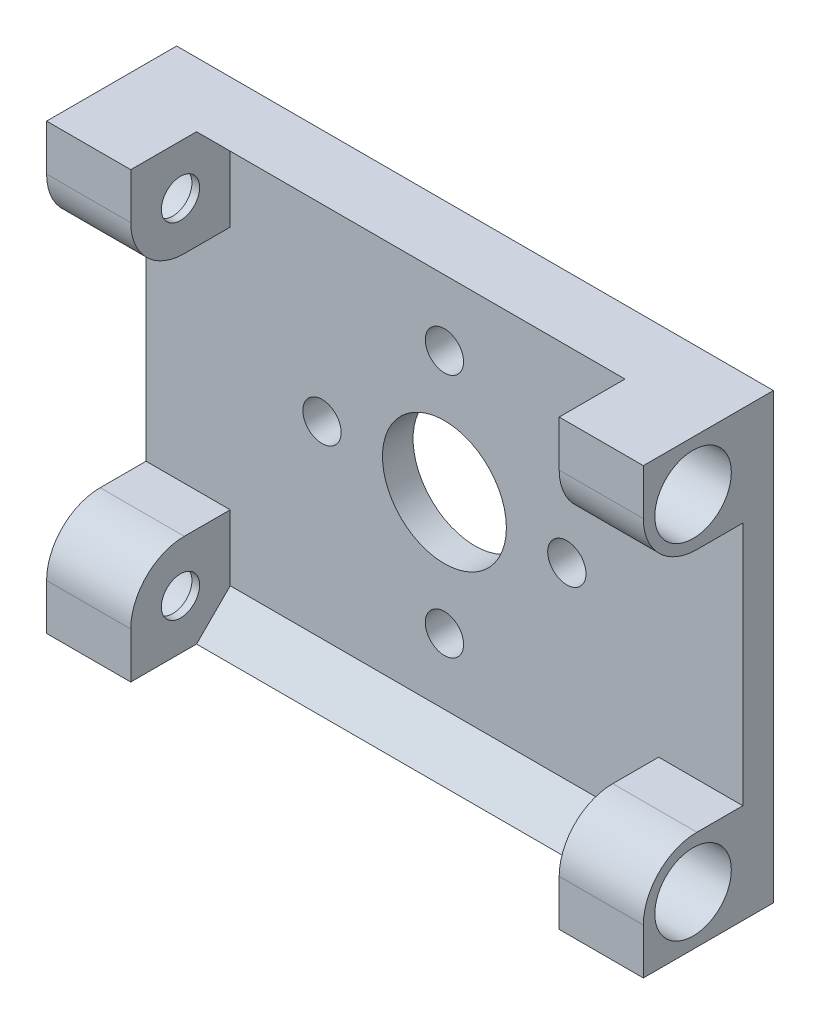
SolidWorks part; units mm, degrees
ref_plane "Front Plane" through (0, 0, 0) normal (0, 0, 1) x (1, 0, 0)
ref_plane "Top Plane" through (0, 0, 0) normal (0, 1, 0) x (1, 0, 0)
ref_plane "Right Plane" through (0, 0, 0) normal (1, 0, 0) x (0, 0, -1)
sketch "Sketch1" plane through (0, 0, 0) normal (0, 0, 1) x (1, 0, 0)
  line L5 (19.5, 0.8564) -> (-19.5, -22.8564) construction
  line L6 (19.5, -22.8564) -> (-19.5, 0.8564) construction
  line L7 (19.5, -22.8564) -> (-19.5, -22.8564)
  line L8 (19.5, -22.8564) -> (19.5, 0.8564)
  line L9 (19.5, 0.8564) -> (-19.5, 0.8564)
  line L10 (-19.5, -22.8564) -> (-19.5, 0.8564)
  line L11 (19.5, -22.8564) -> (-19.5, 0.8564) construction
  line L12 (19.5, 0.8564) -> (-19.5, -22.8564) construction
  arc A5 (1.25, -19) -> (-1.25, -19) centre (0, -19) ccw construction
  arc A6 (-1.25, -19) -> (1.25, -19) centre (0, -19) ccw construction
  arc A7 (1.25, -19) -> (-1.25, -19) centre (0, -19) ccw
  arc A8 (-1.25, -19) -> (1.25, -19) centre (0, -19) ccw
  arc A9 (-6.75, -11) -> (-9.25, -11) centre (-8, -11) ccw construction
  arc A10 (-6.75, -11) -> (-9.25, -11) centre (-8, -11) ccw
  arc A11 (-9.25, -11) -> (-6.75, -11) centre (-8, -11) ccw construction
  arc A12 (-9.25, -11) -> (-6.75, -11) centre (-8, -11) ccw
  arc A13 (1.25, -3) -> (-1.25, -3) centre (0, -3) ccw construction
  arc A14 (-1.25, -3) -> (1.25, -3) centre (0, -3) ccw construction
  arc A15 (1.25, -3) -> (-1.25, -3) centre (0, -3) ccw
  arc A16 (-1.25, -3) -> (1.25, -3) centre (0, -3) ccw
  arc A17 (9.25, -11) -> (6.75, -11) centre (8, -11) ccw construction
  arc A18 (6.75, -11) -> (9.25, -11) centre (8, -11) ccw construction
  arc A19 (9.25, -11) -> (6.75, -11) centre (8, -11) ccw
  arc A20 (6.75, -11) -> (9.25, -11) centre (8, -11) ccw
  point P0 (0, -11)
  point P8 (0, -11)
extrude "Boss-Extrude1" add sketch "Sketch1" along normal blind 2
sketch "Sketch9" plane through (0, 0, 2) normal (0, 0, 1) x (1, 0, 0)
  circle A0 centre (0, -11) radius 4.05
extrude "Cut-Extrude6" cut sketch "Sketch9" against normal blind 5
sketch "Sketch10" plane through (-19.5, 0, 0) normal (-1, 0, 0) x (0, 0, 1)
  line L0 (4.2, 3.5) -> (8.5, 3.5)
  line L1 (8.5, 3.5) -> (8.5, 0.5)
  line L2 (5, -3) -> (2, -3)
  line L3 (2, 0.8564) -> (2, -22.8564) construction
  line L4 (2, -3) -> (5, -3) construction
  line L5 (2, -3) -> (2, 0.8564)
  line L6 (2, 0.8564) -> (0, 0.8564)
  line L7 (0, 0.8564) -> (0, 3.5)
  line L8 (4.2, 3.5) -> (0, 3.5)
  line L9 (2, -11) -> (11.2, -11) construction
  line L10 (11.2, -17.2) -> (11.2, -4.8) construction
  line L11 (5, -19) -> (2, -19)
  line L12 (2, -19) -> (2, -22.8564)
  line L13 (2, -22.8564) -> (0, -22.8564)
  line L14 (0, -22.8564) -> (0, -25.5)
  line L15 (4.2, -25.5) -> (0, -25.5)
  line L16 (4.2, -25.5) -> (8.5, -25.5)
  line L17 (8.5, -25.5) -> (8.5, -22.5)
  arc A0 (5, -3) -> (8.5, 0.5) centre (5, 0.5) ccw construction
  arc A1 (5, -3) -> (8.5, 0.5) centre (5, 0.5) ccw
  circle A2 centre (5.25, 0.25) radius 1.25
  circle A3 centre (5.25, -22.25) radius 1.25
  arc A4 (5, -19) -> (8.5, -22.5) centre (5, -22.5) cw
  dimension "D1" = 2.5
extrude "Boss-Extrude5" add sketch "Sketch10" against normal up to surface (5.5 mm away)
sketch "Sketch11" plane through (-19.5, 0, 0) normal (-1, 0, 0) x (0, 0, 1)
  line L0 (3.2, -11) -> (11.2, -11) construction
  line L1 (3.2, -4.8) -> (3.2, -17.2) construction
  line L2 (11.2, -17.2) -> (11.2, -4.8) construction
  circle A0 centre (5.25, 0.25) radius 2.5
  circle A1 centre (5.25, -22.25) radius 2.5
  dimension "D1" = 5
extrude "Cut-Extrude7" cut sketch "Sketch11" against normal blind 5
sketch "Sketch12" plane through (19.5, 0, 0) normal (1, 0, 0) x (0, 0, -1)
  line L4 (-5, -3) -> (-2, -3)
  line L6 (-5, -3) -> (-2, -3)
  line L8 (-2, -3) -> (-2, -19)
  line L12 (0, -25.5) -> (0, 3.5)
  line L14 (-8.5, 3.5) -> (-8.5, 0.5)
  line L15 (-8.5, 3.5) -> (-8.5, 0.5)
  line L16 (-2, -3) -> (-2, -19)
  line L20 (0, -25.5) -> (0, 3.5)
  line L24 (0, 3.5) -> (-8.5, 3.5)
  line L25 (0, 3.5) -> (-8.5, 3.5)
  line L26 (-8.5, -25.5) -> (0, -25.5)
  line L27 (-8.5, -25.5) -> (0, -25.5)
  line L28 (-8.5, -22.5) -> (-8.5, -25.5)
  line L29 (-8.5, -22.5) -> (-8.5, -25.5)
  line L30 (-2, -19) -> (-5, -19)
  line L31 (-2, -19) -> (-5, -19)
  circle A0 centre (-5.25, -22.25) radius 2.5 construction
  circle A1 centre (-5.25, 0.25) radius 2.5 construction
  circle A6 centre (-5.25, -22.25) radius 2.5
  circle A7 centre (-5.25, 0.25) radius 2.5
  arc A8 (-8.5, 0.5) -> (-5, -3) centre (-5, 0.5) ccw
  arc A9 (-8.5, 0.5) -> (-5, -3) centre (-5, 0.5) ccw
  arc A10 (-5, -19) -> (-8.5, -22.5) centre (-5, -22.5) ccw
  arc A11 (-5, -19) -> (-8.5, -22.5) centre (-5, -22.5) ccw
  dimension "D1" = 0
extrude "Boss-Extrude6" add sketch "Sketch12" against normal up to surface (5.5 mm away) contours L20 L25 L15 A9 L6 L16 L31 A11 L29 L27 | A6 | A7
sketch "Sketch13" plane through (14, 0, 0) normal (-1, 0, 0) x (0, 0, 1)
  line L0 (0, 3.5) -> (4.2, 3.5)
  line L1 (0, 3.5) -> (8.5, 3.5) construction
  line L2 (4.2, 3.5) -> (2, 1.3) construction
  line L3 (4.2, 3.5) -> (2, 1.3)
  line L4 (2, 1.3) -> (2, 0.8564)
  line L5 (2, 0.8564) -> (0, 0.8564)
  line L6 (0, 0.8564) -> (0, 3.5)
  line L7 (3.2, -11) -> (11.2, -11) construction
  line L8 (3.2, -4.8) -> (3.2, -17.2) construction
  line L9 (11.2, -17.2) -> (11.2, -4.8) construction
  line L10 (2, -22.8564) -> (0, -22.8564)
  line L11 (2, -23.3) -> (2, -22.8564)
  line L12 (4.2, -25.5) -> (2, -23.3)
  line L13 (0, -25.5) -> (4.2, -25.5)
  line L14 (0, -22.8564) -> (0, -25.5)
extrude "Boss-Extrude7" add sketch "Sketch13" along normal up to surface (28 mm away) up to face at (-14, 0.3554, 3.8178)
